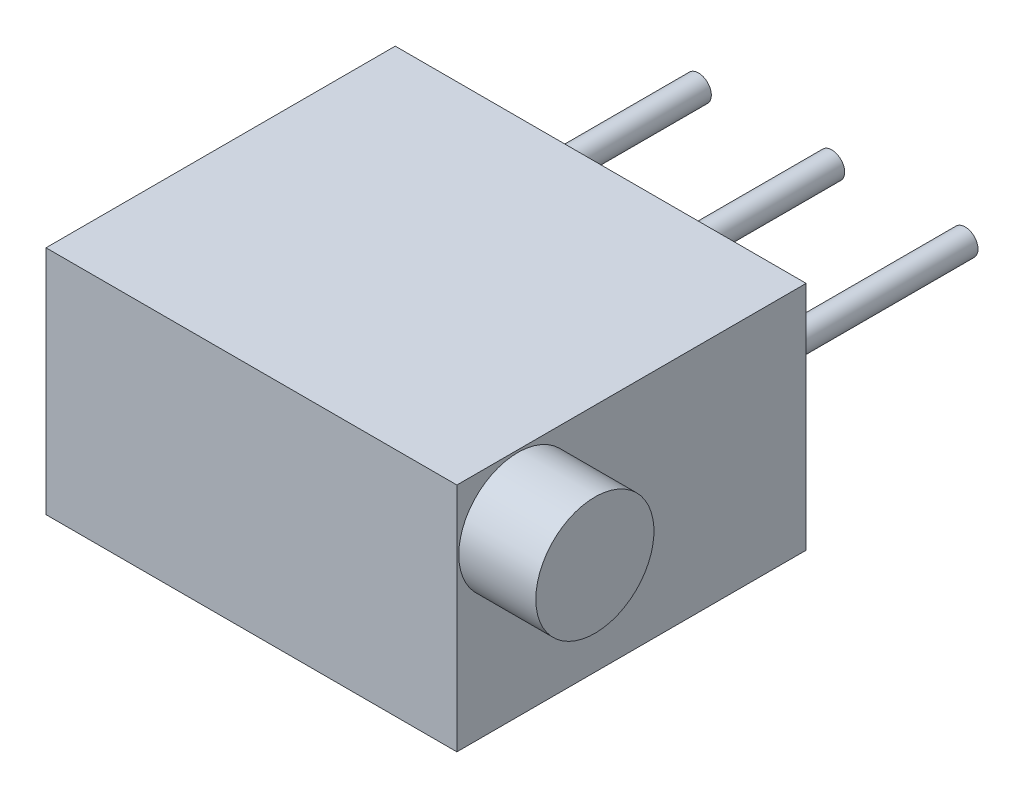
SolidWorks part; units mm, degrees
ref_plane "前视" through (0, 0, 0) normal (0, 0, 1) x (1, 0, 0)
ref_plane "上视" through (0, 0, 0) normal (0, 1, 0) x (1, 0, 0)
ref_plane "右视" through (0, 0, 0) normal (1, 0, 0) x (0, 0, -1)
sketch "草图1" plane through (0, 0, 0) normal (0, 1, 0) x (1, 0, 0)
  line L0 (0, 81.3418) -> (0, -101.3275) construction
  line L1 (-87.3375, 0) -> (113.7186, 0) construction
  line L3 (-4, 3.4) -> (4, 3.4)
  line L4 (-4, 3.4) -> (-4, -3.4)
  line L5 (-4, -3.4) -> (4, -3.4)
  line L6 (4, 3.4) -> (4, -3.4)
  dimension "D1" = 8
  dimension "D2" = 6.8
extrude "拉伸1" add sketch "草图1" along normal blind 4.5
sketch "草图3" plane through (0, 0, -3.4) normal (0, 0, -1) x (-1, 0, 0)
  line L0 (-5.1663, 2.25) -> (6.6013, 2.25) construction
  line L2 (0, 5.9307) -> (0, -2.165) construction
  circle A0 centre (0, 2.25) radius 0.25
  circle A1 centre (2.596, 2.25) radius 0.25
  circle A2 centre (-2.596, 2.25) radius 0.25
  dimension "D1" = 0.5
extrude "拉伸3" add sketch "草图3" along normal blind 4.5
sketch "草图4" plane through (4, 0, -0.6) normal (-1, 0, 0) x (0, 0, 1)
  circle A0 centre (2.8131, 3.3048) radius 1.15
  dimension "D1" = 2.3
extrude "拉伸4" add sketch "草图4" against normal blind 1.5
